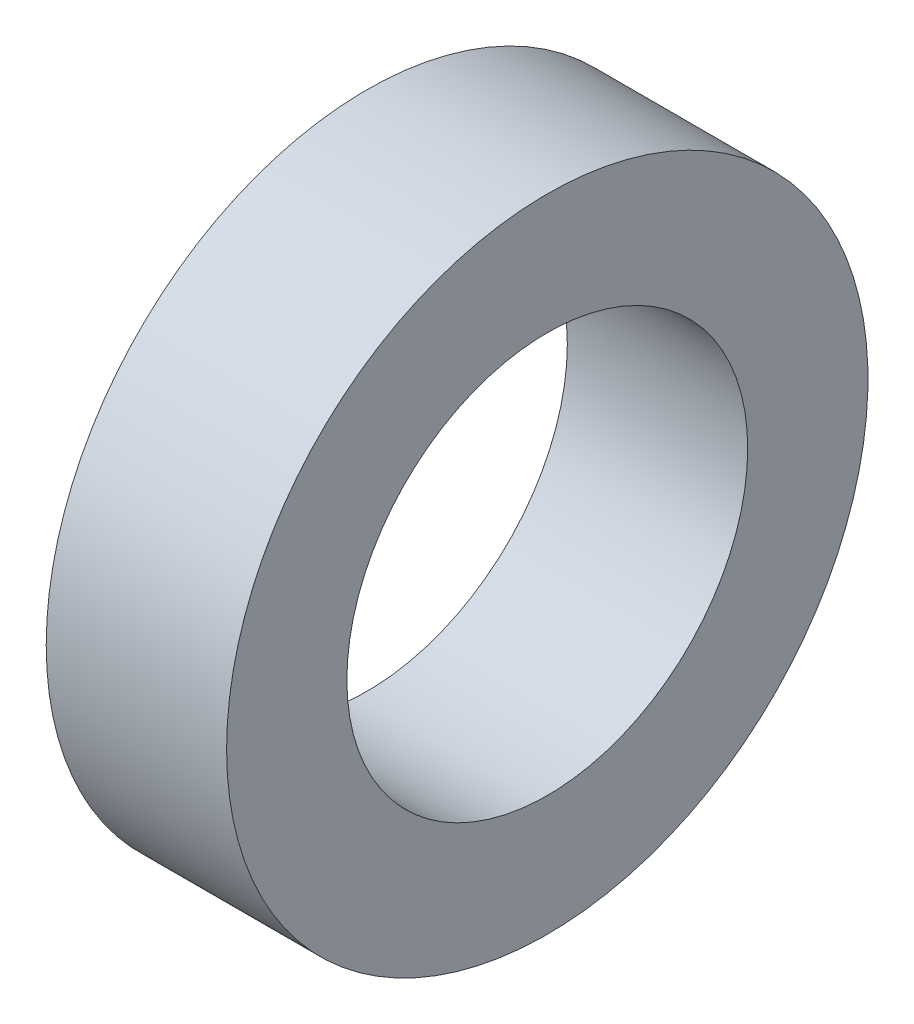
SolidWorks part; units mm, degrees
ref_plane "Спереди" through (0, 0, 0) normal (0, 0, 1) x (1, 0, 0)
ref_plane "Сверху" through (0, 0, 0) normal (0, 1, 0) x (1, 0, 0)
ref_plane "Справа" through (0, 0, 0) normal (1, 0, 0) x (0, 0, -1)
sketch "Эскиз1" plane through (0, 0, 0) normal (0, 0, 1) x (1, 0, 0)
  line L0 (-51.709, 6.8559) -> (56.5816, 6.8559) construction
  line L2 (-7.4278, 14.8559) -> (-2.9278, 14.8559)
  line L3 (-7.4278, 14.8559) -> (-7.4278, 11.8559)
  line L4 (-7.4278, 11.8559) -> (-2.9278, 11.8559)
  line L5 (-2.9278, 14.8559) -> (-2.9278, 11.8559)
  dimension "D1" = 8
  dimension "D2" = 4.5
  dimension "D3" = 3
revolve "Повернуть1" add sketch "Эскиз1" angle 360 about L0
